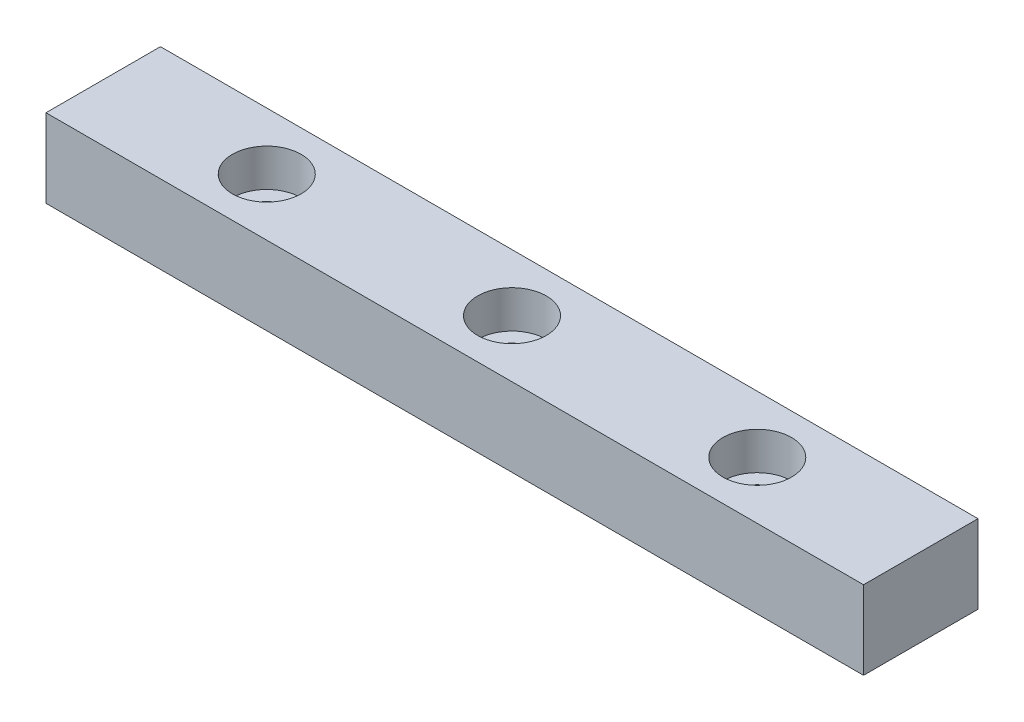
SolidWorks part; units mm, degrees
ref_plane "前视基准面" through (0, 0, 0) normal (0, 0, 1) x (1, 0, 0)
ref_plane "上视基准面" through (0, 0, 0) normal (0, 1, 0) x (1, 0, 0)
ref_plane "右视基准面" through (0, 0, 0) normal (1, 0, 0) x (0, 0, -1)
other "Configuration Table"
sketch "草图1" plane through (0, 0, 0) normal (0, 1, 0) x (1, 0, 0)
  line L1 (-25, 3.5) -> (25, 3.5)
  line L2 (-25, 3.5) -> (-25, -3.5)
  line L3 (-25, -3.5) -> (25, -3.5)
  line L4 (25, 3.5) -> (25, -3.5)
  line L5 (-25, 3.5) -> (25, -3.5) construction
  line L6 (-25, -3.5) -> (25, 3.5) construction
  point P4 (0, 0)
  dimension "D1" = 7
  dimension "D2" = 50
extrude "凸台-拉伸1" add sketch "草图1" along normal blind 4.8
sketch "草图2" plane through (0, 4.8, 0) normal (0, 1, 0) x (1, 0, 0)
  line L0 (-15, 0) -> (15, 0) construction
  circle A0 centre (0, 0) radius 2.1
  circle A1 centre (-15, 0) radius 2.1
  circle A2 centre (15, 0) radius 2.1
  dimension "D1" = 4.2
  dimension "D2" = 15
  dimension "D3" = 15
extrude "切除-拉伸1" cut sketch "草图2" against normal blind 2.3
sketch "草图3" plane through (0, 2.5, 0) normal (0, 1, 0) x (1, 0, 0)
  circle A0 centre (0, 0) radius 1.2
  circle A1 centre (-15, 0) radius 1.2
  circle A2 centre (15, 0) radius 1.2
  circle A5 centre (-15, 0) radius 2.1 construction
  dimension "D1" = 2.4
extrude "切除-拉伸2" cut sketch "草图3" against normal through all
